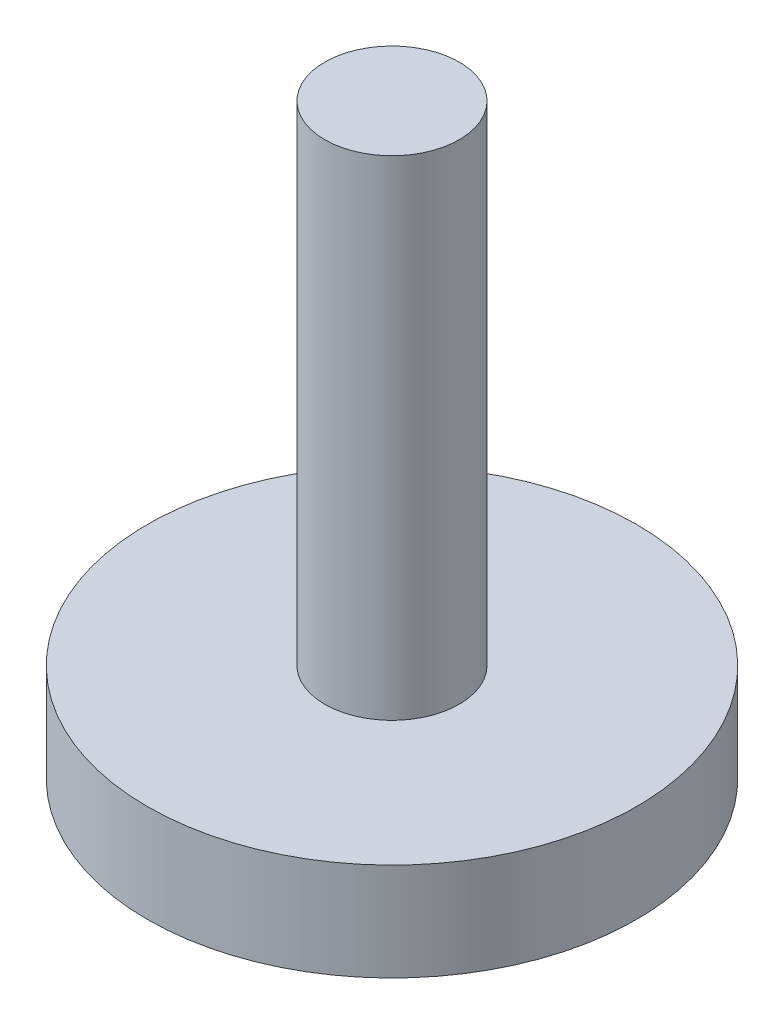
SolidWorks part; units mm, degrees
ref_plane "Front" through (0, 0, 0) normal (0, 0, 1) x (1, 0, 0)
ref_plane "Top" through (0, 0, 0) normal (0, 1, 0) x (1, 0, 0)
ref_plane "Right" through (0, 0, 0) normal (1, 0, 0) x (0, 0, -1)
sketch "스케치1" plane through (0, 0, 0) normal (0, 1, 0) x (1, 0, 0)
  circle A0 centre (0, 0) radius 7.5
  dimension "D1" = 15
extrude "보스-돌출1" add sketch "스케치1" along normal blind 3
sketch "스케치2" plane through (0, 3, 0) normal (0, 1, 0) x (1, 0, 0)
  circle A0 centre (0, 0) radius 2.0625
  dimension "D1" = 4.125
extrude "보스-돌출2" add sketch "스케치2" along normal blind 15
